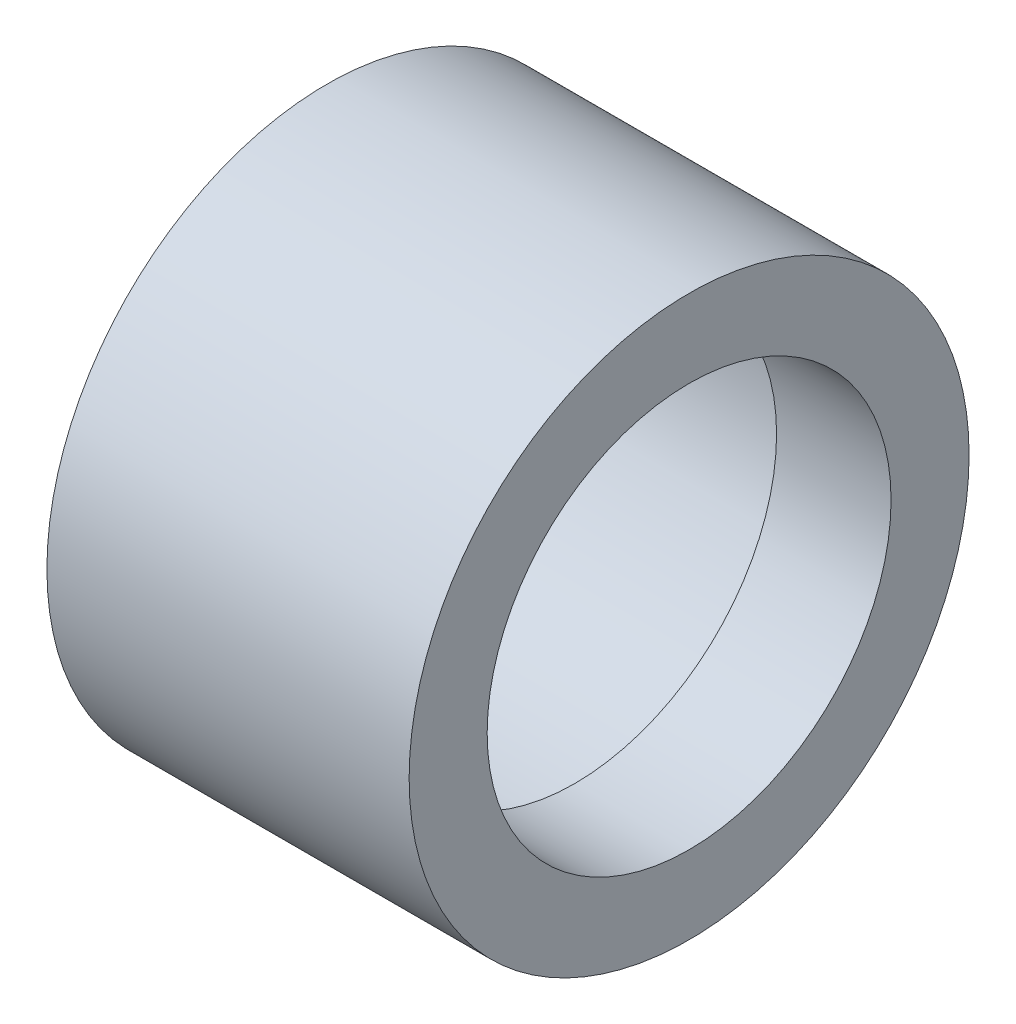
SolidWorks part; units mm, degrees
ref_plane "Front Plane" through (0, 0, 0) normal (0, 0, 1) x (1, 0, 0)
ref_plane "Top Plane" through (0, 0, 0) normal (0, 1, 0) x (1, 0, 0)
ref_plane "Right Plane" through (0, 0, 0) normal (1, 0, 0) x (0, 0, -1)
sketch "Sketch14" plane through (0, 0, 0) normal (1, 0, 0) x (0, 0, -1)
  circle A0 centre (0, 0) radius 30.5
  dimension "D1" = 61
extrude "Boss-Extrude11" add sketch "Sketch14" along normal blind 39.4589 separate body
sketch "Sketch13" plane through (0, 0, 0) normal (-1, 0, 0) x (0, 0, 1)
  circle A1 centre (0, 0) radius 26.9875
  circle A2 centre (0, 0) radius 30.5 construction
  dimension "D1" = 53.975
sketch "Sketch15" plane through (0, 0, 0) normal (-1, 0, 0) x (0, 0, 1)
  circle A0 centre (0, 0) radius 22
  circle A1 centre (0, 0) radius 26.9875 construction
  dimension "D1" = 44
extrude "Cut-Extrude2" cut sketch "Sketch15" against normal through all
extrude "Cut-Extrude3" cut sketch "Sketch13" against normal blind 26.9875
